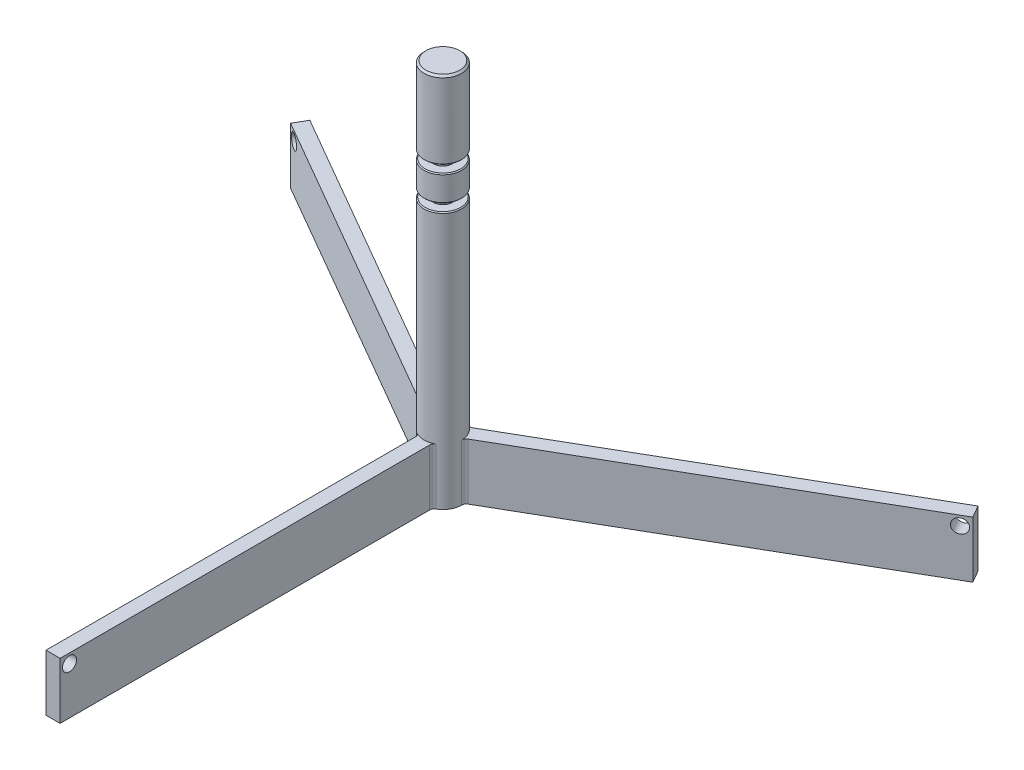
SolidWorks part; units mm, degrees
ref_plane "Front" through (0, 0, 0) normal (0, 0, 1) x (1, 0, 0)
ref_plane "Top" through (0, 0, 0) normal (0, 1, 0) x (1, 0, 0)
ref_plane "Right" through (0, 0, 0) normal (1, 0, 0) x (0, 0, -1)
other "Configuration Table"
sketch "Sketch5" plane through (0, 0, 0) normal (0, 0, 1) x (1, 0, 0)
  line L0 (0, 112.3855) -> (0, -102.7942) construction
  line L1 (12.7, 173.99) -> (6.35, 173.99)
  line L2 (0, 0) -> (12.7, 0)
  line L3 (0, 0) -> (0, 254)
  line L4 (0, 254) -> (12.7, 254)
  line L5 (12.7, 0) -> (12.7, 173.99)
  line L6 (6.35, 173.99) -> (6.35, 179.07)
  line L7 (6.35, 179.07) -> (12.7, 179.07)
  line L8 (12.7, 196.596) -> (6.35, 196.596)
  line L9 (6.35, 196.596) -> (6.35, 201.676)
  line L10 (6.35, 201.676) -> (12.7, 201.676)
  line L11 (12.7, 179.07) -> (12.7, 196.596)
  line L12 (12.7, 201.676) -> (12.7, 254)
  dimension "D1" = 254
  dimension "D2" = 12.7
  dimension "D3" = 6.35
  dimension "D4" = 5.08
  dimension "D5" = 74.93
  dimension "D6" = 52.324
revolve "Base-Revolve" add sketch "Sketch5" angle 360 about L0
sketch "Sketch6" plane through (0, 0, 0) normal (0, 0, 1) x (1, 0, 0)
  line L1 (-4.7625, 0) -> (4.7625, 0)
  line L2 (-4.7625, 0) -> (-4.7625, 38.1)
  line L3 (-4.7625, 38.1) -> (4.7625, 38.1)
  line L4 (4.7625, 0) -> (4.7625, 38.1)
  point P4 (0, 0)
  dimension "D1" = 38.1
  dimension "D2" = 9.525
extrude "Boss-Extrude2" add sketch "Sketch6" along normal blind 263.525
sketch "Sketch7" plane through (4.7625, 0, 0) normal (1, 0, 0) x (0, 0, -1)
  line L0 (-263.525, 0) -> (-263.525, 38.1) construction
  line L1 (-263.525, 38.1) -> (-11.7732, 38.1) construction
  circle A0 centre (-257.175, 31.75) radius 4.7625
  dimension "D1" = 9.525
  dimension "D2" = 6.35
  dimension "D3" = 6.35
extrude "Cut-Extrude2" cut sketch "Sketch7" against normal through all
fillet "Fillet2" radius 3.175 2 edges at (-4.7625, 19.05, 11.7732) (4.7625, 19.05, 11.7732)
pattern_circular "CirPattern2" count 3 over 360 about axis through (0, 0, 0) along (0, 1, 0) of "Fillet2", "Cut-Extrude2", "Boss-Extrude2"
chamfer "Chamfer5" distance 0.635 angle 45 4 edges at (0, 179.07, 12.7) (0, 196.596, 12.7) (0, 201.676, 12.7) (0, 173.99, 12.7)
chamfer "Chamfer6" distance 1.27 angle 45 1 edges at (0, 254, 12.7)
